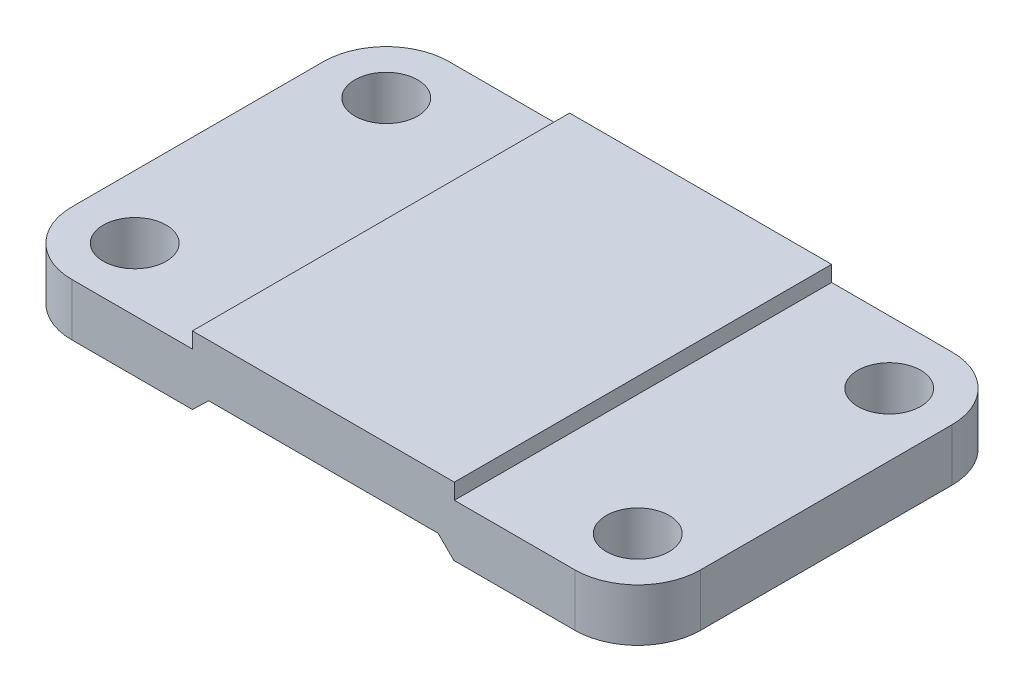
SolidWorks part; units mm, degrees
ref_plane "Front Plane" through (0, 0, 0) normal (0, 0, 1) x (1, 0, 0)
ref_plane "Top Plane" through (0, 0, 0) normal (0, 1, 0) x (1, 0, 0)
ref_plane "Right Plane" through (0, 0, 0) normal (1, 0, 0) x (0, 0, -1)
sketch "Sketch1" plane through (0, 0, 0) normal (0, 1, 0) x (1, 0, 0)
  line L1 (0, 36) -> (48, 36)
  line L2 (0, 36) -> (-48, 36)
  line L3 (-60, 24) -> (-60, -24)
  line L4 (-48, -36) -> (48, -36)
  line L5 (60, -24) -> (60, 24)
  line L7 (0, -55) -> (0, 55) construction
  line L8 (-55, 0) -> (55, 0) construction
  circle A0 centre (-48, 24) radius 6
  arc A1 (-48, 36) -> (-60, 24) centre (-48, 24) ccw
  circle A2 centre (48, 24) radius 6
  arc A3 (48, 36) -> (60, 24) centre (48, 24) cw
  arc A4 (48, -36) -> (60, -24) centre (48, -24) ccw
  circle A5 centre (48, -24) radius 6
  arc A6 (-48, -36) -> (-60, -24) centre (-48, -24) cw
  circle A7 centre (-48, -24) radius 6
  dimension "D6" = 12
extrude "Boss-Extrude1" add sketch "Sketch1" along normal blind 10
sketch "Sketch2" plane through (0, 10, 0) normal (0, 1, 0) x (1, 0, 0)
  line L2 (-25, 11.0417) -> (-25, 36)
  line L3 (48, 36) -> (-48, 36) construction
  line L4 (-25, 36) -> (-25, -36)
  line L5 (-48, -36) -> (48, -36) construction
  line L6 (-25, -36) -> (25, -36)
  line L7 (25, -36) -> (25, 36)
  line L8 (25, 36) -> (-25, 36)
  line M6 (48, 36) -> (-48, 36)
  line M10 (-48, -36) -> (48, -36)
  dimension "D2" = 50
  dimension "D3" = 50
extrude "Boss-Extrude2" add sketch "Sketch2" along normal blind 3 contours L7 L2 L4 M10 M6
sketch "Sketch7" plane through (0, 0, 36) normal (0, 0, 1) x (1, 0, 0)
  line L1 (-48, 0) -> (48, 0) construction
  line L5 (-21.8986, 3) -> (21.9, 3)
  line L6 (-25, 0) -> (24.9, 0)
  line L7 (-25, 0) -> (-21.8986, 3)
  line L9 (21.9, 3) -> (24.9, 0)
extrude "Cut-Extrude6" cut sketch "Sketch7" against normal blind 500
